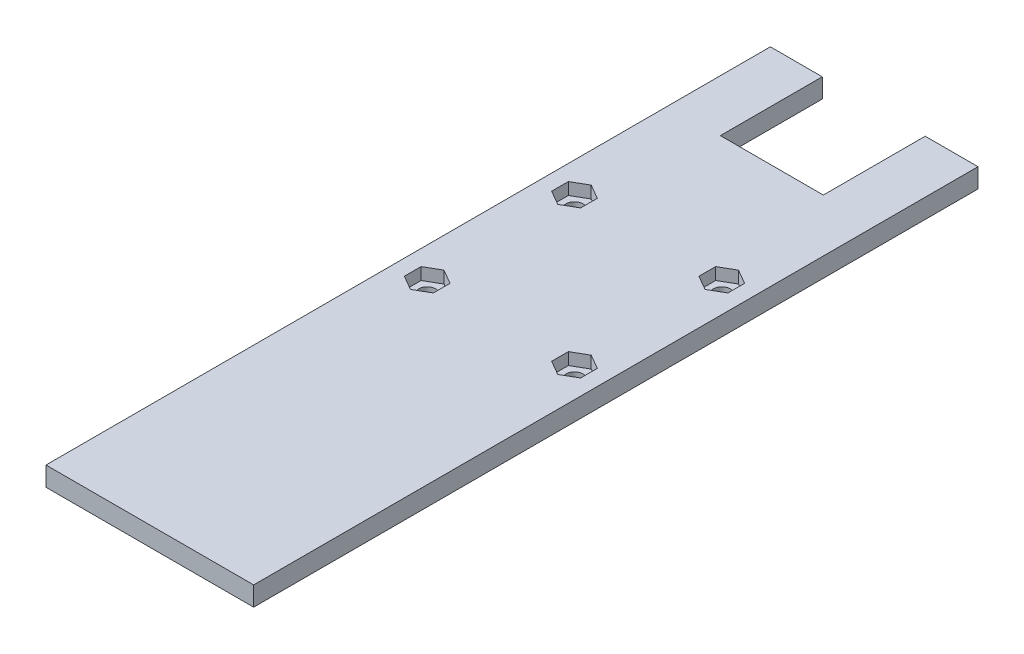
SolidWorks part; units mm, degrees
material "ABS"
ref_plane "Front Plane" through (0, 0, 0) normal (0, 0, 1) x (1, 0, 0)
ref_plane "Top Plane" through (0, 0, 0) normal (0, 1, 0) x (1, 0, 0)
ref_plane "Right Plane" through (0, 0, 0) normal (1, 0, 0) x (0, 0, -1)
sketch "Sketch1" plane through (0, 0, 0) normal (0, 1, 0) x (1, 0, 0)
  line L1 (21.5, -75) -> (-21.5, -75)
  line L2 (21.5, -75) -> (21.5, 75)
  line L3 (21.5, 75) -> (-21.5, 75)
  line L4 (-21.5, -75) -> (-21.5, 75)
  line L5 (21.5, -75) -> (-21.5, 75) construction
  line L6 (21.5, 75) -> (-21.5, -75) construction
  point P0 (0, 0)
  dimension "D1" = 43
  dimension "D2" = 150
extrude "Boss-Extrude1" add sketch "Sketch1" along normal blind 4
sketch "Sketch2" plane through (0, 4, 0) normal (0, 1, 0) x (1, 0, 0)
  line L0 (21.5, 75) -> (0, 75) construction
  line L1 (21.5, 75) -> (-21.5, 75) construction
  line L2 (0, 75) -> (0, 53.9) construction
  line L4 (0, 53.9) -> (10.57, 53.9)
  line L5 (0, 53.9) -> (0, 75)
  line L6 (0, 75) -> (10.57, 75)
  line L7 (10.57, 53.9) -> (10.57, 75)
  line L8 (0, 53.9) -> (-10.75, 53.9)
  line L9 (0, 53.9) -> (0, 75)
  line L10 (0, 75) -> (-10.75, 75)
  line L11 (-10.75, 53.9) -> (-10.75, 75)
  dimension "D1" = 21.5
  dimension "D2" = 21.1
  dimension "D3" = 10.57
  dimension "D4" = 10.75
  dimension "D5" = 21.1
extrude "Cut-Extrude1" cut sketch "Sketch2" against normal through all contours L9 L8 L11 L10 | L5 L4 L7 L6
sketch "Sketch3" plane through (0, 4, 0) normal (0, 1, 0) x (1, 0, 0)
  line L0 (21.5, 75) -> (15.25, 75) construction
  line L1 (21.5, 75) -> (10.57, 75) construction
  line L2 (15.25, 75) -> (15.25, 28.19) construction
  line L3 (0, -2.31) -> (0, 28.19) construction
  line L4 (15.25, 28.19) -> (-15.25, 28.19) construction
  line L5 (15.25, 28.19) -> (15.25, -2.31) construction
  line L6 (15.25, -2.31) -> (-15.25, -2.31) construction
  line L7 (-15.25, 28.19) -> (-15.25, -2.31) construction
  line L8 (-15.25, 31.6541) -> (-18.25, 29.9221)
  line L9 (-18.25, 29.9221) -> (-18.25, 26.4579)
  line L10 (-18.25, 26.4579) -> (-15.25, 24.7259)
  line L11 (-15.25, 24.7259) -> (-12.25, 26.4579)
  line L12 (-12.25, 26.4579) -> (-12.25, 29.9221)
  line L13 (-12.25, 29.9221) -> (-15.25, 31.6541)
  line L14 (-15.25, 12.94) -> (15.25, 12.94) construction
  line L15 (12.25, 29.9221) -> (15.25, 31.6541)
  line L16 (12.25, 26.4579) -> (12.25, 29.9221)
  line L17 (15.25, 24.7259) -> (12.25, 26.4579)
  line L18 (18.25, 26.4579) -> (15.25, 24.7259)
  line L19 (18.25, 29.9221) -> (18.25, 26.4579)
  line L20 (15.25, 31.6541) -> (18.25, 29.9221)
  line L21 (12.25, -0.5779) -> (12.25, -4.0421)
  line L22 (15.25, 1.1541) -> (12.25, -0.5779)
  line L23 (18.25, -0.5779) -> (15.25, 1.1541)
  line L24 (18.25, -4.0421) -> (18.25, -0.5779)
  line L25 (15.25, -5.7741) -> (18.25, -4.0421)
  line L26 (12.25, -4.0421) -> (15.25, -5.7741)
  line L27 (-12.25, -4.0421) -> (-15.25, -5.7741)
  line L28 (-12.25, -0.5779) -> (-12.25, -4.0421)
  line L29 (-15.25, 1.1541) -> (-12.25, -0.5779)
  line L30 (-18.25, -0.5779) -> (-15.25, 1.1541)
  line L31 (-18.25, -4.0421) -> (-18.25, -0.5779)
  line L32 (-15.25, -5.7741) -> (-18.25, -4.0421)
  circle A1 centre (-15.25, 28.19) radius 3 construction
  dimension "D1" = 6.25
  dimension "D2" = 46.81
  dimension "D3" = 30.5
  dimension "D4" = 30.5
  dimension "D5" = 6
extrude "Cut-Extrude2" cut sketch "Sketch3" against normal blind 2.5
sketch "Sketch4" plane through (0, 4, 0) normal (0, 1, 0) x (1, 0, 0)
  line L0 (-18.25, 12.94) -> (18.25, 12.94) construction
  line L1 (-18.25, 29.9221) -> (18.25, 29.9221) construction
  line L2 (-18.25, 29.9221) -> (-18.25, -4.0421) construction
  line L3 (-18.25, -4.0421) -> (18.25, -4.0421) construction
  line L4 (18.25, 29.9221) -> (18.25, -4.0421) construction
  line L5 (0, 29.9221) -> (0, -4.0421) construction
  line L6 (-15.25, 24.7259) -> (-15.25, 31.6541) construction
  circle A0 centre (-15.25, 28.19) radius 1.75
  circle A1 centre (15.25, 28.19) radius 1.75
  circle A2 centre (15.25, -2.31) radius 1.75
  circle A3 centre (-15.25, -2.31) radius 1.75
  dimension "D1" = 3.5
extrude "Cut-Extrude3" cut sketch "Sketch4" against normal through all
